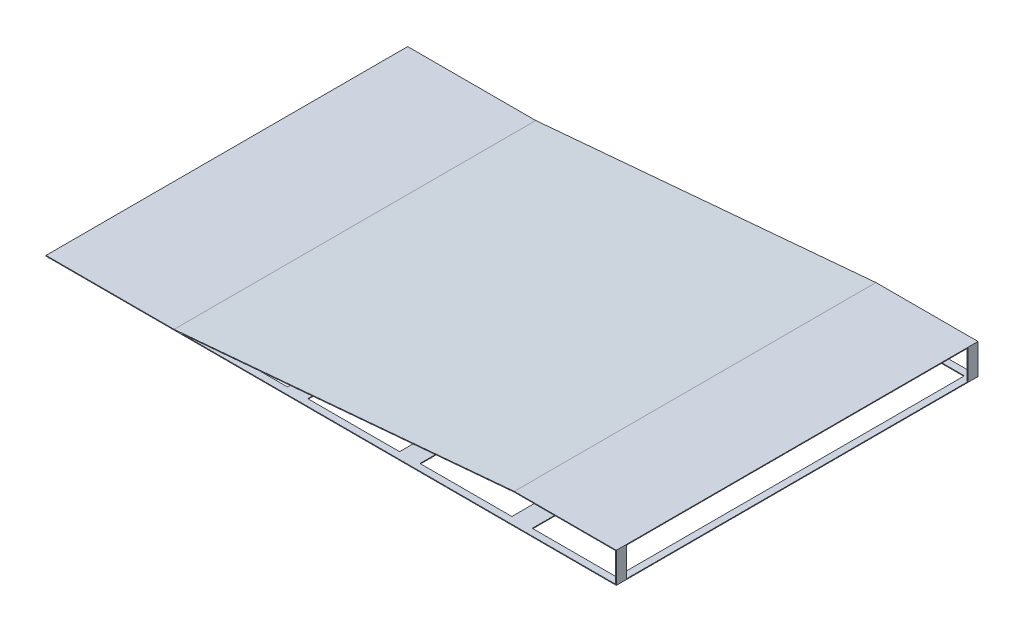
SolidWorks part; units mm, degrees
material "Cast Alloy Steel"
ref_plane "Front Plane" through (0, 0, 0) normal (0, 0, 1) x (1, 0, 0)
ref_plane "Top Plane" through (0, 0, 0) normal (0, 1, 0) x (1, 0, 0)
ref_plane "Right Plane" through (0, 0, 0) normal (1, 0, 0) x (0, 0, -1)
sketch "Sketch1" plane through (0, 0, 0) normal (0, 0, 1) x (1, 0, 0)
  line L0 (6882.5, 447.4433) -> (1882.5, 10)
  line L1 (8382.5, 0) -> (8382.5, 447.4433)
  line L2 (8382.5, 447.4433) -> (6882.5, 447.4433)
  line L3 (8382.5, 0) -> (0, 0)
  line L4 (1882.5, 10) -> (0, 10)
  line L5 (0, 10) -> (0, 0)
  line L6 (1882.5, 10) -> (8382.5, 10) construction
  dimension "D1" = 5
  dimension "D2" = 8382.5
  dimension "D3" = 10
  dimension "D4" = 6500
  dimension "D5" = 1500
extrude "Boss-Extrude1" add sketch "Sketch1" along normal blind 5316
sketch "Sketch2" plane through (0, 0, 5316) normal (0, 0, 1) x (1, 0, 0)
  line L14 (8372.5, 10) -> (8372.5, 437.4433)
  line L15 (8372.5, 437.4433) -> (6882.9366, 437.4433)
  line L16 (1997.2371, 10) -> (8372.5, 10)
  line L17 (6882.9366, 437.4433) -> (1997.2371, 10)
  line L18 (8372.5, 10) -> (8372.5, 437.4433)
  line L19 (8372.5, 437.4433) -> (6882.9366, 437.4433)
  line L20 (1997.2371, 10) -> (8372.5, 10)
  line L21 (6882.9366, 437.4433) -> (1997.2371, 10)
  dimension "D1" = 10
extrude "Cut-Extrude1" cut sketch "Sketch2" against normal through all
sketch "Sketch3" plane through (0, 0, 0) normal (0, -1, 0) x (1, 0, 0)
  line L0 (5097.2371, 5216) -> (5097.2371, 100)
  line L1 (5397.2371, 5216) -> (5397.2371, 100)
  line L2 (6747.2371, 5216) -> (6747.2371, 100)
  line L3 (7047.2371, 5216) -> (7047.2371, 100)
  line L6 (1997.2371, 5216) -> (1997.2371, 100)
  line L7 (1997.2371, 0) -> (1997.2371, 5316) construction
  line L8 (2097.2371, 5216) -> (2097.2371, 100)
  line L9 (0, 100) -> (8282.5, 100)
  line L10 (8282.5, 100) -> (8282.5, 5216)
  line L11 (8282.5, 5216) -> (0, 5216)
  line L12 (0, 100) -> (8282.5, 100)
  line L13 (8282.5, 100) -> (8282.5, 5216)
  line L14 (8282.5, 5216) -> (0, 5216)
  line L16 (3447.2371, 5216) -> (3747.2371, 5216)
  line L17 (3447.2371, 5216) -> (3447.2371, 100)
  line L18 (3447.2371, 100) -> (3747.2371, 100)
  line L19 (3747.2371, 5216) -> (3747.2371, 100)
  dimension "D3" = 1350
  dimension "D4" = 300
  dimension "D5" = 1350
  dimension "D6" = 300
  dimension "D7" = 1350
  dimension "D8" = 300
  dimension "D1" = 100
  dimension "D2" = 100
extrude "Cut-Extrude2" cut sketch "Sketch3" against normal blind 10 contours L17 L14 L8 L12 | L14 L19 L12 L0 | L13 L14 L1 L12 | L2 L14 L1 L12
sketch "Sketch5" plane through (8382.5, 0, 0) normal (1, 0, 0) x (0, 0, -1)
  line L29 (-5316, 437.4433) -> (0, 437.4433)
  line L30 (-5316, 437.4433) -> (0, 437.4433)
  line L32 (-5316, 10) -> (0, 10)
  line L33 (-5316, 10) -> (0, 10)
  line L38 (-5166, 0) -> (-5166, 447.4433)
  line L39 (-5166, 0) -> (-5166, 447.4433)
  line L41 (-150, 0) -> (-150, 447.4433)
  line L42 (-150, 0) -> (-150, 447.4433)
  line L43 (-5166, 437.4433) -> (-150, 437.4433)
  line L44 (-5166, 437.4433) -> (-5166, 10)
  line L45 (-5166, 10) -> (-150, 10)
  line L46 (-150, 437.4433) -> (-150, 10)
  dimension "D1" = 10
  dimension "D2" = 10
  dimension "D3" = 150
  dimension "D4" = 150
extrude "Cut-Extrude4" cut sketch "Sketch5" against normal blind 100 contours L33 L42 L30 L39
